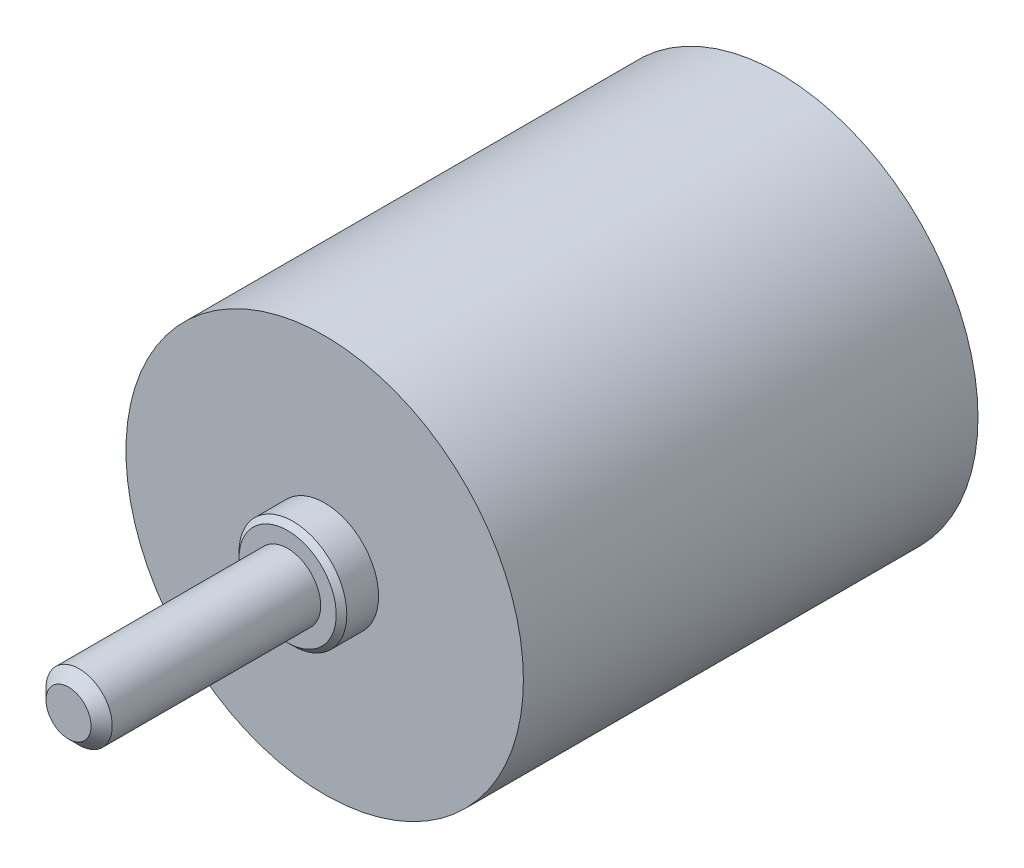
SolidWorks part; units mm, degrees
ref_plane "Front Plane" through (0, 0, 0) normal (0, 0, 1) x (1, 0, 0)
ref_plane "Top Plane" through (0, 0, 0) normal (0, 1, 0) x (1, 0, 0)
ref_plane "Right Plane" through (0, 0, 0) normal (1, 0, 0) x (0, 0, -1)
sketch "Sketch1" plane through (0, 0, 0) normal (1, 0, 0) x (0, 0, -1)
  line L0 (0, 0) -> (0, 3.175)
  line L1 (0, 3.175) -> (21, 3.175)
  line L2 (21, 3.175) -> (21, 5.1689)
  line L3 (21, 5.1689) -> (24.556, 5.1689)
  line L4 (24.556, 5.1689) -> (24.556, 19.05)
  line L5 (24.556, 19.05) -> (68.1347, 19.05)
  line L6 (68.1347, 19.05) -> (68.1347, 5.1689)
  line L7 (68.1347, 5.1689) -> (72.7964, 5.1689)
  line L8 (72.7964, 5.1689) -> (72.7964, 0)
  line L9 (0, 0) -> (72.7964, 0) construction
  line L10 (0, 0) -> (72.7964, 0)
  point P3 (70.4656, 5.1689)
  dimension "D1" = 6.35
  dimension "D2" = 38.1
  dimension "D3" = 21
  dimension "D4" = 3.556
  dimension "D5" = 10.3378
  dimension "D6" = 10.3378
  dimension "D7" = 72.7964
revolve "Revolve1" add sketch "Sketch1" angle 360 about L9
chamfer "Chamfer1" distance 1.016 angle 45 1 edges at (3.175, 0, 0)
chamfer "Chamfer2" distance 0.508 angle 45 2 edges at (5.1689, 0, -21) (5.1689, 0, -72.7964)
